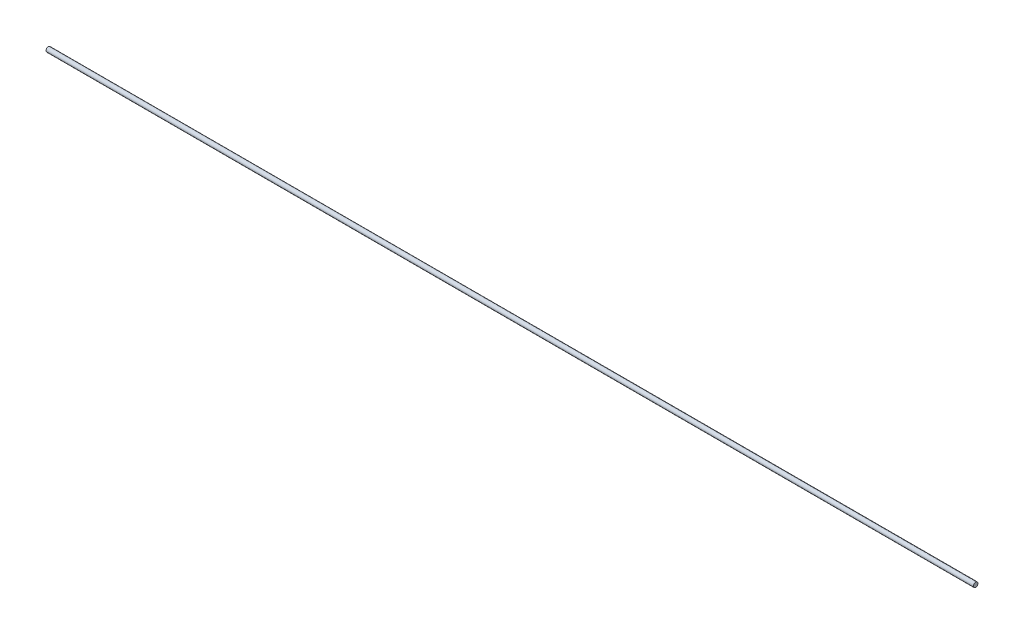
SolidWorks part; units mm, degrees
ref_plane "정면" through (0, 0, 0) normal (0, 0, 1) x (1, 0, 0)
ref_plane "윗면" through (0, 0, 0) normal (0, 1, 0) x (1, 0, 0)
ref_plane "우측면" through (0, 0, 0) normal (1, 0, 0) x (0, 0, -1)
sketch "스케치1" plane through (0, 0, 0) normal (1, 0, 0) x (0, 0, -1)
  circle A0 centre (0, 0) radius 1.5
  dimension "D1" = 3
extrude "보스-돌출1" add sketch "스케치1" along normal blind 600
